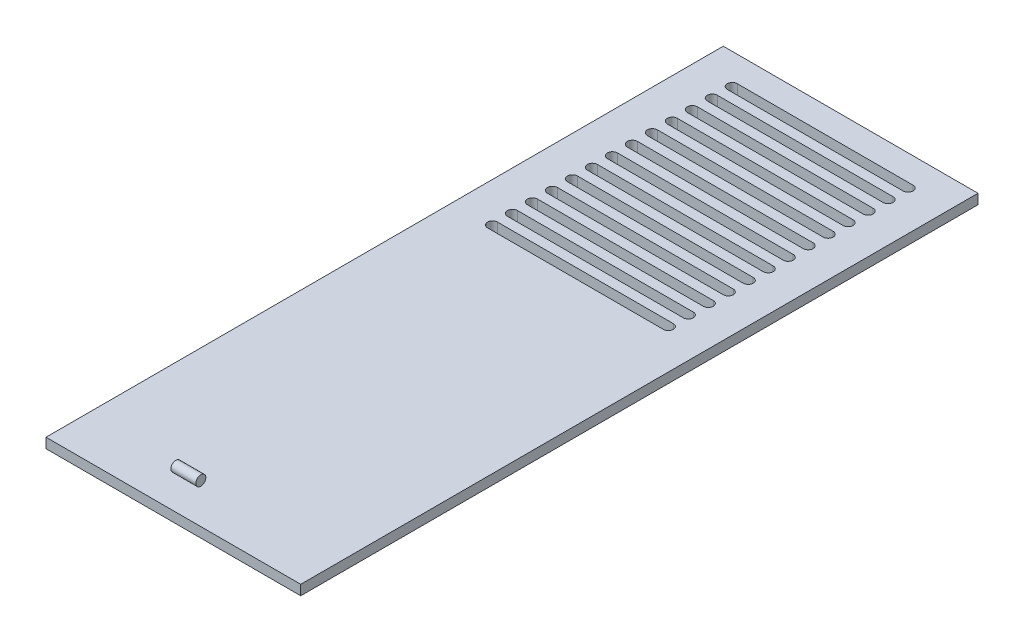
SolidWorks part; units mm, degrees
ref_plane "Front Plane" through (0, 0, 0) normal (0, 0, 1) x (1, 0, 0)
ref_plane "Top Plane" through (0, 0, 0) normal (0, 1, 0) x (1, 0, 0)
ref_plane "Right Plane" through (0, 0, 0) normal (1, 0, 0) x (0, 0, -1)
sketch "Sketch1" plane through (0, 0, 0) normal (0, 1, 0) x (1, 0, 0)
  line L1 (-56, 63.4545) -> (-5, 63.4545)
  line L2 (-56, 63.4545) -> (-56, -72.5455)
  line L3 (-56, -72.5455) -> (-5, -72.5455)
  line L4 (-5, 63.4545) -> (-5, -72.5455)
  dimension "D1" = 136
  dimension "D2" = 51
extrude "Boss-Extrude1" add sketch "Sketch1" along normal blind 2
sketch "Sketch3" plane through (0, 2, 0) normal (0, 1, 0) x (1, 0, 0)
  line L0 (-5, 63.4545) -> (-56, 63.4545) construction
  line L1 (-49.1, 58.3545) -> (-11.9, 58.3545)
  line L2 (-49.1, 58.3545) -> (-49.1, 8.4545)
  line L3 (-49.1, 8.4545) -> (-11.9, 8.4545)
  line L4 (-11.9, 58.3545) -> (-11.9, 8.4545)
  dimension "D1" = 5.1
  dimension "D2" = 37.2
  dimension "D4" = 49.9
sketch "Sketch4" plane through (0, 2, 0) normal (0, 1, 0) x (1, 0, 0)
  line L0 (-48.1, 57.3545) -> (-12.9, 57.3545) construction
  line L1 (-48.1, 58.3545) -> (-12.9, 58.3545)
  line L2 (-48.1, 56.3545) -> (-12.9, 56.3545)
  line L3 (-49.1, 58.3545) -> (-49.1, 8.4545) construction
  line L4 (-49.1, 58.3545) -> (-11.9, 58.3545) construction
  line L5 (-48.1, 53.3545) -> (-12.9, 53.3545) construction
  line L6 (-48.1, 54.3545) -> (-12.9, 54.3545)
  line L7 (-48.1, 52.3545) -> (-12.9, 52.3545)
  line L8 (-48.1, 49.3545) -> (-12.9, 49.3545) construction
  line L9 (-48.1, 50.3545) -> (-12.9, 50.3545)
  line L10 (-48.1, 48.3545) -> (-12.9, 48.3545)
  line L11 (-48.1, 45.3545) -> (-12.9, 45.3545) construction
  line L12 (-48.1, 46.3545) -> (-12.9, 46.3545)
  line L13 (-48.1, 44.3545) -> (-12.9, 44.3545)
  line L14 (-48.1, 41.3545) -> (-12.9, 41.3545) construction
  line L15 (-48.1, 42.3545) -> (-12.9, 42.3545)
  line L16 (-48.1, 40.3545) -> (-12.9, 40.3545)
  line L17 (-48.1, 37.3545) -> (-12.9, 37.3545) construction
  line L18 (-48.1, 38.3545) -> (-12.9, 38.3545)
  line L19 (-48.1, 36.3545) -> (-12.9, 36.3545)
  line L20 (-48.1, 33.3545) -> (-12.9, 33.3545) construction
  line L21 (-48.1, 34.3545) -> (-12.9, 34.3545)
  line L22 (-48.1, 32.3545) -> (-12.9, 32.3545)
  line L23 (-48.1, 29.3545) -> (-12.9, 29.3545) construction
  line L24 (-48.1, 30.3545) -> (-12.9, 30.3545)
  line L25 (-48.1, 28.3545) -> (-12.9, 28.3545)
  line L26 (-48.1, 25.3545) -> (-12.9, 25.3545) construction
  line L27 (-48.1, 26.3545) -> (-12.9, 26.3545)
  line L28 (-48.1, 24.3545) -> (-12.9, 24.3545)
  line L29 (-48.1, 21.3545) -> (-12.9, 21.3545) construction
  line L30 (-48.1, 22.3545) -> (-12.9, 22.3545)
  line L31 (-48.1, 20.3545) -> (-12.9, 20.3545)
  line L32 (-48.1, 17.3545) -> (-12.9, 17.3545) construction
  line L33 (-48.1, 18.3545) -> (-12.9, 18.3545)
  line L34 (-48.1, 16.3545) -> (-12.9, 16.3545)
  line L35 (-48.1, 13.3545) -> (-12.9, 13.3545) construction
  line L36 (-48.1, 14.3545) -> (-12.9, 14.3545)
  line L37 (-48.1, 12.3545) -> (-12.9, 12.3545)
  line L38 (-48.1, 9.3545) -> (-12.9, 9.3545) construction
  line L39 (-48.1, 10.3545) -> (-12.9, 10.3545)
  line L40 (-48.1, 8.3545) -> (-12.9, 8.3545)
  arc A0 (-48.1, 58.3545) -> (-48.1, 56.3545) centre (-48.1, 57.3545) ccw
  arc A1 (-12.9, 56.3545) -> (-12.9, 58.3545) centre (-12.9, 57.3545) ccw
  arc A2 (-48.1, 54.3545) -> (-48.1, 52.3545) centre (-48.1, 53.3545) ccw
  arc A3 (-12.9, 52.3545) -> (-12.9, 54.3545) centre (-12.9, 53.3545) ccw
  arc A4 (-48.1, 50.3545) -> (-48.1, 48.3545) centre (-48.1, 49.3545) ccw
  arc A5 (-12.9, 48.3545) -> (-12.9, 50.3545) centre (-12.9, 49.3545) ccw
  arc A6 (-48.1, 46.3545) -> (-48.1, 44.3545) centre (-48.1, 45.3545) ccw
  arc A7 (-12.9, 44.3545) -> (-12.9, 46.3545) centre (-12.9, 45.3545) ccw
  arc A8 (-48.1, 42.3545) -> (-48.1, 40.3545) centre (-48.1, 41.3545) ccw
  arc A9 (-12.9, 40.3545) -> (-12.9, 42.3545) centre (-12.9, 41.3545) ccw
  arc A10 (-48.1, 38.3545) -> (-48.1, 36.3545) centre (-48.1, 37.3545) ccw
  arc A11 (-12.9, 36.3545) -> (-12.9, 38.3545) centre (-12.9, 37.3545) ccw
  arc A12 (-48.1, 34.3545) -> (-48.1, 32.3545) centre (-48.1, 33.3545) ccw
  arc A13 (-12.9, 32.3545) -> (-12.9, 34.3545) centre (-12.9, 33.3545) ccw
  arc A14 (-48.1, 30.3545) -> (-48.1, 28.3545) centre (-48.1, 29.3545) ccw
  arc A15 (-12.9, 28.3545) -> (-12.9, 30.3545) centre (-12.9, 29.3545) ccw
  arc A16 (-48.1, 26.3545) -> (-48.1, 24.3545) centre (-48.1, 25.3545) ccw
  arc A17 (-12.9, 24.3545) -> (-12.9, 26.3545) centre (-12.9, 25.3545) ccw
  arc A18 (-48.1, 22.3545) -> (-48.1, 20.3545) centre (-48.1, 21.3545) ccw
  arc A19 (-12.9, 20.3545) -> (-12.9, 22.3545) centre (-12.9, 21.3545) ccw
  arc A20 (-48.1, 18.3545) -> (-48.1, 16.3545) centre (-48.1, 17.3545) ccw
  arc A21 (-12.9, 16.3545) -> (-12.9, 18.3545) centre (-12.9, 17.3545) ccw
  arc A22 (-48.1, 14.3545) -> (-48.1, 12.3545) centre (-48.1, 13.3545) ccw
  arc A23 (-12.9, 12.3545) -> (-12.9, 14.3545) centre (-12.9, 13.3545) ccw
  arc A24 (-48.1, 10.3545) -> (-48.1, 8.3545) centre (-48.1, 9.3545) ccw
  arc A25 (-12.9, 8.3545) -> (-12.9, 10.3545) centre (-12.9, 9.3545) ccw
  point P2 (-30.5, 57.3545)
  point P7 (-49.1, 57.3545)
  point P16 (-30.5, 53.3545)
  point P23 (-30.5, 49.3545)
  point P30 (-30.5, 45.3545)
  point P37 (-30.5, 41.3545)
  point P44 (-30.5, 37.3545)
  point P51 (-30.5, 33.3545)
  point P58 (-30.5, 29.3545)
  point P65 (-30.5, 25.3545)
  point P72 (-30.5, 21.3545)
  point P79 (-30.5, 17.3545)
  point P86 (-30.5, 13.3545)
  point P93 (-30.5, 9.3545)
  dimension "D1" = 0
  dimension "D3" = 13
  dimension "D2" = 0
extrude "Cut-Extrude1" cut sketch "Sketch4" against normal blind 10
sketch "Sketch5" plane through (0, 0, -63.4545) normal (0, 0, -1) x (-1, 0, 0)
  line L1 (56, 2) -> (57, 2)
  line L2 (56, 2) -> (56, 0)
  line L3 (56, 0) -> (57, 0)
  line L4 (57, 2) -> (57, 0)
  line L5 (5, 2) -> (4, 2)
  line L6 (5, 2) -> (5, 0)
  line L7 (5, 0) -> (4, 0)
  line L8 (4, 2) -> (4, 0)
  point P10 (57, 1)
  dimension "D1" = 1
  dimension "D2" = 1
extrude "Boss-Extrude2" add sketch "Sketch5" against normal up to surface (136 mm away) up to face at (-30.5, 1, 72.5455)
sketch "Sketch6" plane through (0, 0, -63.4545) normal (0, 0, -1) x (-1, 0, 0)
  line L1 (57, 0) -> (58, 0)
  line L2 (57, 0) -> (57, 2)
  line L3 (57, 2) -> (58, 2)
  line L4 (58, 0) -> (58, 2)
  line L5 (4, 0) -> (3, 0)
  line L6 (4, 0) -> (4, 2)
  line L7 (4, 2) -> (3, 2)
  line L8 (3, 0) -> (3, 2)
  dimension "D1" = 1
  dimension "D2" = 1
extrude "Boss-Extrude3" add sketch "Sketch6" against normal up to surface (136 mm away) up to face at (-30.5, 1, 72.5455)
sketch "Sketch7" plane through (0, 0, 72.5455) normal (0, 0, 1) x (1, 0, 0)
  line L1 (-66.7377, 9.812) -> (2.0582, 9.812)
  line L2 (-66.7377, 9.812) -> (-66.7377, -16.6136)
  line L3 (-66.7377, -16.6136) -> (2.0582, -16.6136)
  line L4 (2.0582, 9.812) -> (2.0582, -16.6136)
extrude "Cut-Extrude2" cut sketch "Sketch7" against normal blind 0.4
sketch "Sketch8" plane through (0, 0, -63.4545) normal (0, 0, -1) x (-1, 0, 0)
  line L0 (3, 0) -> (58, 0) construction
  line L1 (3, 2) -> (5, 2)
  line L2 (3, 2) -> (3, 0)
  line L3 (3, 0) -> (5, 0)
  line L4 (5, 2) -> (5, 0)
  line L6 (58, 2) -> (56, 2)
  line L7 (58, 2) -> (58, 0)
  line L8 (58, 0) -> (56, 0)
  line L9 (56, 2) -> (56, 0)
  dimension "D1" = 2
  dimension "D2" = 2
extrude "Cut-Extrude3" cut sketch "Sketch8" against normal blind 135.6
ref_plane "Plane1" through (-30.5, 0, 0) normal (-1, 0, 0) x (0, 0, 1)
sketch "Sketch9" plane through (-30.5, 0, 0) normal (-1, 0, 0) x (0, 0, 1)
  line L0 (72.1455, 2) -> (-63.4545, 2) construction
  line L1 (72.1455, 2) -> (72.1455, 0) construction
  circle A0 centre (69.1455, 7) radius 1
  dimension "D1" = 2
  dimension "D2" = 5
  dimension "D3" = 3
extrude "Boss-Extrude4" add sketch "Sketch9" along normal mid plane 5 separate body
